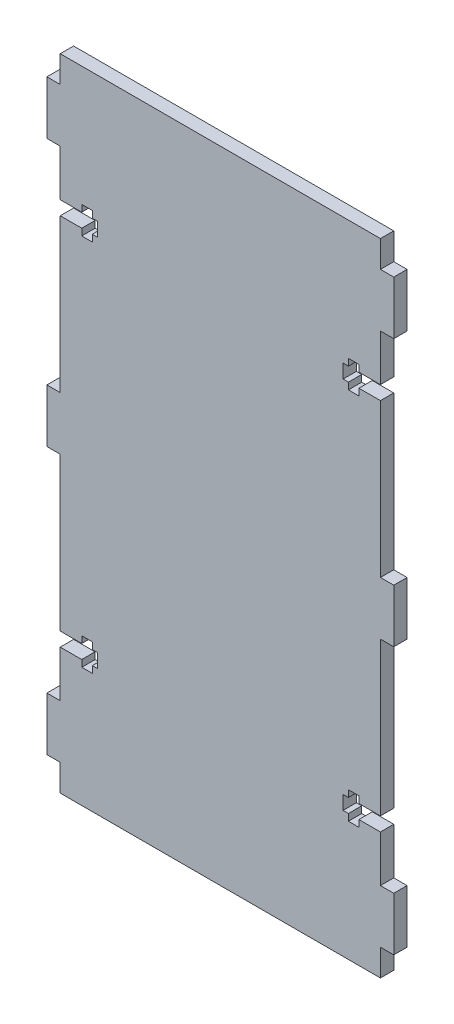
SolidWorks part; units mm, degrees
ref_plane "Front Plane" through (0, 0, 0) normal (0, 0, 1) x (1, 0, 0)
ref_plane "Top Plane" through (0, 0, 0) normal (0, 1, 0) x (1, 0, 0)
ref_plane "Right Plane" through (0, 0, 0) normal (1, 0, 0) x (0, 0, -1)
sketch "Sketch1" plane through (0, 0, 0) normal (0, 0, 1) x (1, 0, 0)
  line L1 (0, 0) -> (76.2, 0)
  line L2 (0, 0) -> (0, 152.4)
  line L3 (0, 152.4) -> (76.2, 152.4)
  line L4 (76.2, 0) -> (76.2, 152.4)
  dimension "D1" = 152.4
  dimension "D2" = 76.2
extrude "Boss-Extrude1" add sketch "Sketch1" along normal blind 3.175
sketch "Sketch2" plane through (0, 0, 3.175) normal (0, 0, 1) x (1, 0, 0)
  line L0 (0, 76.2) -> (76.2, 76.2) construction
  line L1 (0, 146.05) -> (-3.175, 146.05)
  line L2 (0, 146.05) -> (0, 133.35)
  line L3 (0, 133.35) -> (-3.175, 133.35)
  line L4 (-3.175, 146.05) -> (-3.175, 133.35)
  line L5 (0, 6.35) -> (-3.175, 6.35)
  line L6 (0, 6.35) -> (0, 19.05)
  line L7 (0, 19.05) -> (-3.175, 19.05)
  line L8 (-3.175, 6.35) -> (-3.175, 19.05)
  line L9 (0, 152.4) -> (0, 0) construction
  line L10 (76.2, 0) -> (76.2, 152.4) construction
  line L11 (-3.175, 76.2) -> (0, 76.2) construction
  line L12 (0, 82.55) -> (-3.175, 82.55)
  line L13 (0, 82.55) -> (0, 69.85)
  line L14 (0, 69.85) -> (-3.175, 69.85)
  line L15 (-3.175, 82.55) -> (-3.175, 69.85)
  line L16 (38.1, 152.4) -> (38.1, 0) construction
  line L17 (76.2, 152.4) -> (0, 152.4) construction
  line L18 (0, 0) -> (76.2, 0) construction
  line L19 (79.375, 146.05) -> (79.375, 133.35)
  line L20 (76.2, 133.35) -> (79.375, 133.35)
  line L21 (76.2, 146.05) -> (76.2, 133.35)
  line L22 (76.2, 146.05) -> (79.375, 146.05)
  line L23 (0, 82.55) -> (-3.175, 82.55)
  line L24 (0, 69.85) -> (-3.175, 69.85)
  line L25 (0, 82.55) -> (-3.175, 82.55)
  line L26 (0, 69.85) -> (-3.175, 69.85)
  line L27 (0, 82.55) -> (-3.175, 82.55)
  line L28 (0, 69.85) -> (-3.175, 69.85)
  line L29 (79.375, 6.35) -> (79.375, 19.05)
  line L30 (76.2, 19.05) -> (79.375, 19.05)
  line L31 (76.2, 6.35) -> (76.2, 19.05)
  line L32 (76.2, 6.35) -> (79.375, 6.35)
  line L33 (0, 82.55) -> (-3.175, 82.55)
  line L34 (0, 69.85) -> (-3.175, 69.85)
  line L35 (0, 82.55) -> (-3.175, 82.55)
  line L36 (0, 69.85) -> (-3.175, 69.85)
  line L37 (0, 82.55) -> (-3.175, 82.55)
  line L38 (0, 69.85) -> (-3.175, 69.85)
  line L39 (0, 82.55) -> (-3.175, 82.55)
  line L40 (0, 69.85) -> (-3.175, 69.85)
  line L41 (79.375, 76.2) -> (76.2, 76.2) construction
  line L42 (76.2, 69.85) -> (79.375, 69.85)
  line L43 (76.2, 82.55) -> (79.375, 82.55)
  line L44 (76.2, 69.85) -> (79.375, 69.85)
  line L45 (76.2, 82.55) -> (79.375, 82.55)
  line L46 (76.2, 69.85) -> (79.375, 69.85)
  line L47 (76.2, 82.55) -> (79.375, 82.55)
  line L48 (76.2, 69.85) -> (79.375, 69.85)
  line L49 (76.2, 82.55) -> (79.375, 82.55)
  line L50 (76.2, 69.85) -> (79.375, 69.85)
  line L51 (76.2, 82.55) -> (79.375, 82.55)
  line L52 (76.2, 69.85) -> (79.375, 69.85)
  line L53 (76.2, 82.55) -> (79.375, 82.55)
  line L54 (76.2, 69.85) -> (79.375, 69.85)
  line L55 (76.2, 82.55) -> (79.375, 82.55)
  line L56 (79.375, 82.55) -> (79.375, 69.85)
  line L57 (76.2, 69.85) -> (79.375, 69.85)
  line L58 (76.2, 82.55) -> (76.2, 69.85)
  line L59 (76.2, 82.55) -> (79.375, 82.55)
  line M1 (0, 152.4) -> (0, 0)
  line M3 (76.2, 0) -> (76.2, 152.4)
  dimension "D1" = 3.175
  dimension "D2" = 12.7
  dimension "D3" = 12.7
  dimension "D4" = 12.7
  dimension "D5" = 3.175
  dimension "D6" = 6.35
  dimension "D7" = 6.35
extrude "Boss-Extrude3" add sketch "Sketch2" against normal blind 3.175 contours L12 L15 L14 M1 | L22 L20 L19 M3 | L56 L43 L42 M3 | L32 L29 L30 M3 | L8 L5 L7 M1 | L4 L3 L2 L1
sketch "Sketch4" plane through (0, 0, 3.175) normal (0, 0, 1) x (1, 0, 0)
  line L0 (38.1, 152.4) -> (38.1, 0) construction
  line L1 (76.2, 152.4) -> (0, 152.4) construction
  line L2 (0, 0) -> (76.2, 0) construction
  line L3 (0, 133.35) -> (0, 82.55) construction
  line L4 (0, 122.301) -> (8.89, 122.301)
  line L5 (0, 122.301) -> (0, 118.999)
  line L6 (0, 118.999) -> (8.89, 118.999)
  line L7 (8.89, 122.301) -> (8.89, 118.999)
  line L8 (5.12, 120.65) -> (7.62, 120.65) construction
  line L9 (5.12, 123.9) -> (7.62, 123.9)
  line L10 (5.12, 123.9) -> (5.12, 117.4)
  line L11 (5.12, 117.4) -> (7.62, 117.4)
  line L12 (7.62, 123.9) -> (7.62, 117.4)
  line L13 (0, 120.65) -> (8.89, 120.65) construction
  line L14 (0, 133.35) -> (-3.175, 133.35) construction
  line L15 (-3.175, 76.2) -> (79.375, 76.2) construction
  line L16 (-3.175, 82.55) -> (-3.175, 69.85) construction
  line L17 (79.375, 82.55) -> (79.375, 69.85) construction
  line L18 (0, 31.75) -> (8.89, 31.75) construction
  line L19 (5.12, 31.75) -> (7.62, 31.75) construction
  line L20 (7.62, 28.5) -> (7.62, 35)
  line L21 (5.12, 35) -> (7.62, 35)
  line L22 (5.12, 28.5) -> (5.12, 35)
  line L23 (5.12, 28.5) -> (7.62, 28.5)
  line L24 (8.89, 30.099) -> (8.89, 33.401)
  line L25 (0, 33.401) -> (8.89, 33.401)
  line L26 (0, 30.099) -> (0, 33.401)
  line L27 (0, 30.099) -> (8.89, 30.099)
  line L28 (71.08, 31.75) -> (68.58, 31.75) construction
  line L29 (76.2, 31.75) -> (67.31, 31.75) construction
  line L30 (76.2, 120.65) -> (67.31, 120.65) construction
  line L31 (71.08, 120.65) -> (68.58, 120.65) construction
  line L32 (76.2, 30.099) -> (67.31, 30.099)
  line L33 (76.2, 30.099) -> (76.2, 33.401)
  line L34 (76.2, 33.401) -> (67.31, 33.401)
  line L35 (67.31, 30.099) -> (67.31, 33.401)
  line L36 (71.08, 28.5) -> (68.58, 28.5)
  line L37 (71.08, 28.5) -> (71.08, 35)
  line L38 (71.08, 35) -> (68.58, 35)
  line L39 (68.58, 28.5) -> (68.58, 35)
  line L40 (68.58, 123.9) -> (68.58, 117.4)
  line L41 (71.08, 117.4) -> (68.58, 117.4)
  line L42 (71.08, 123.9) -> (71.08, 117.4)
  line L43 (71.08, 123.9) -> (68.58, 123.9)
  line L44 (67.31, 122.301) -> (67.31, 118.999)
  line L45 (76.2, 118.999) -> (67.31, 118.999)
  line L46 (76.2, 122.301) -> (76.2, 118.999)
  line L47 (76.2, 122.301) -> (67.31, 122.301)
  dimension "D1" = 3.302
  dimension "D2" = 6.5
  dimension "D3" = 2.5
  dimension "D4" = 1.27
  dimension "D5" = 8.89
  dimension "D6" = 12.7
extrude "Cut-Extrude4" cut sketch "Sketch4" against normal blind 3.175 contours L6 L7 L4 L5 | L9 L12 L11 L10 | L21 L20 L23 L22 | L24 L25 L26 L27 | L35 L34 L33 L32 | L38 L39 L36 L37 | L41 L40 L43 L42 | L45 L44 L47 L46
